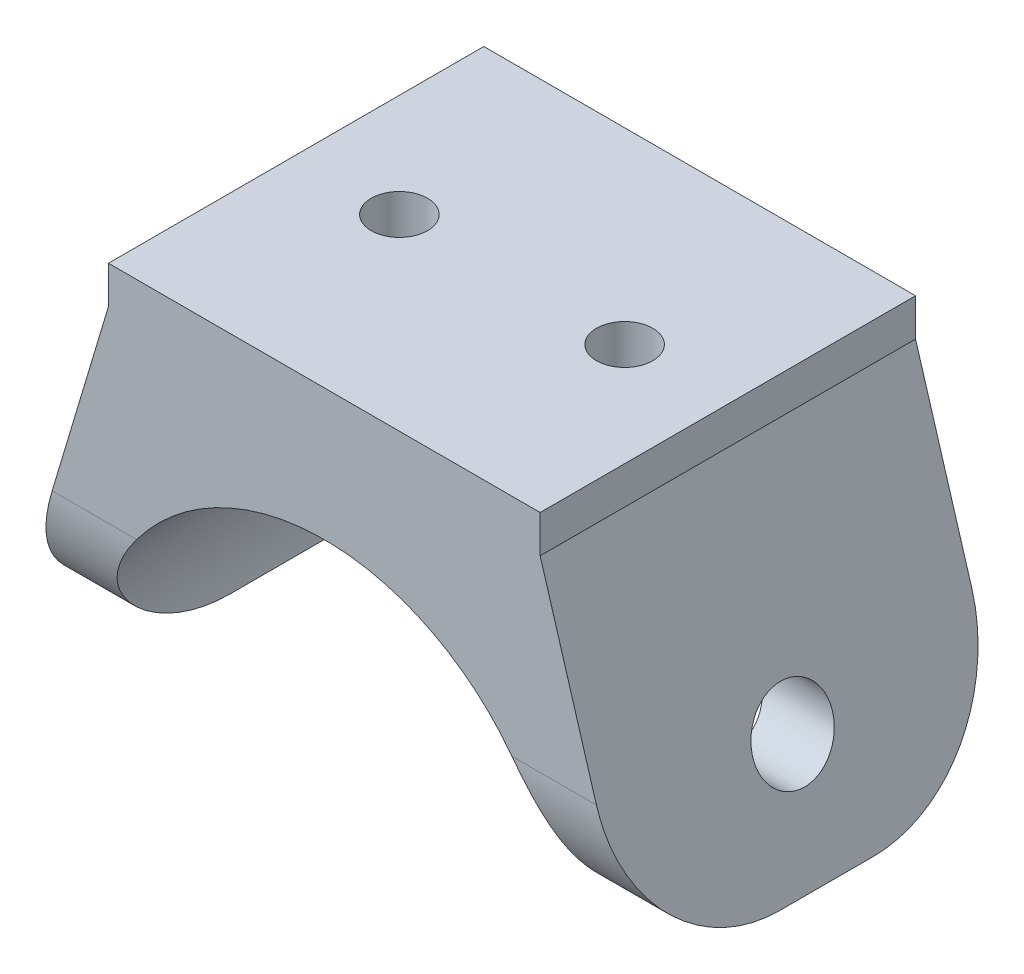
SolidWorks part; units mm, degrees
ref_plane "Front Plane" through (0, 0, 0) normal (0, 0, 1) x (1, 0, 0)
ref_plane "Top Plane" through (0, 0, 0) normal (0, 1, 0) x (1, 0, 0)
ref_plane "Right Plane" through (0, 0, 0) normal (1, 0, 0) x (0, 0, -1)
sketch "Sketch1" plane through (0, 0, 0) normal (0, 0, 1) x (1, 0, 0)
  line L0 (-25, 0) -> (-33.4955, 0)
  line L1 (-33.4955, 0) -> (-23, 35)
  line L2 (-23, 35) -> (-23, 39)
  line L3 (-23, 39) -> (23, 39)
  line L4 (0, 0) -> (0, 62.8742) construction
  line L5 (-33.4955, 0) -> (31.4371, 0) construction
  line L6 (25, 0) -> (33.4955, 0)
  line L7 (23, 35) -> (23, 39)
  line L8 (33.4955, 0) -> (23, 35)
  arc A0 (25, 0) -> (-25, 0) centre (0, 0) ccw
  point P12 (0, 39)
  dimension "D1" = 50
  dimension "D2" = 4
  dimension "D3" = 23
  dimension "D4" = 39
extrude "Boss-Extrude1" add sketch "Sketch1" along normal mid plane 40
fillet "Fillet1" radius 15 4 edges at (-29.2477, 0, 20) (-29.2477, 0, -20) (29.2477, 0, -20) (29.2477, 0, 20)
sketch "Sketch3" plane through (0, 0, 0) normal (1, 0, 0) x (0, 0, -1)
  line L0 (-20, 39) -> (20, 39) construction
  circle A0 centre (0, 12) radius 4.25
  point P4 (0, 0)
  dimension "D1" = 8.5
  dimension "D2" = 27
extrude "Cut-Extrude1" cut sketch "Sketch3" against normal through all both and the other way through all
sketch "Sketch4" plane through (0, 39, 0) normal (0, 1, 0) x (1, 0, 0)
  circle A0 centre (-12, 0) radius 3
  circle A1 centre (12, 0) radius 3
  point P4 (0, 0)
  dimension "D1" = 6
  dimension "D2" = 12
  dimension "D3" = 12
extrude "Cut-Extrude2" cut sketch "Sketch4" against normal blind 14
